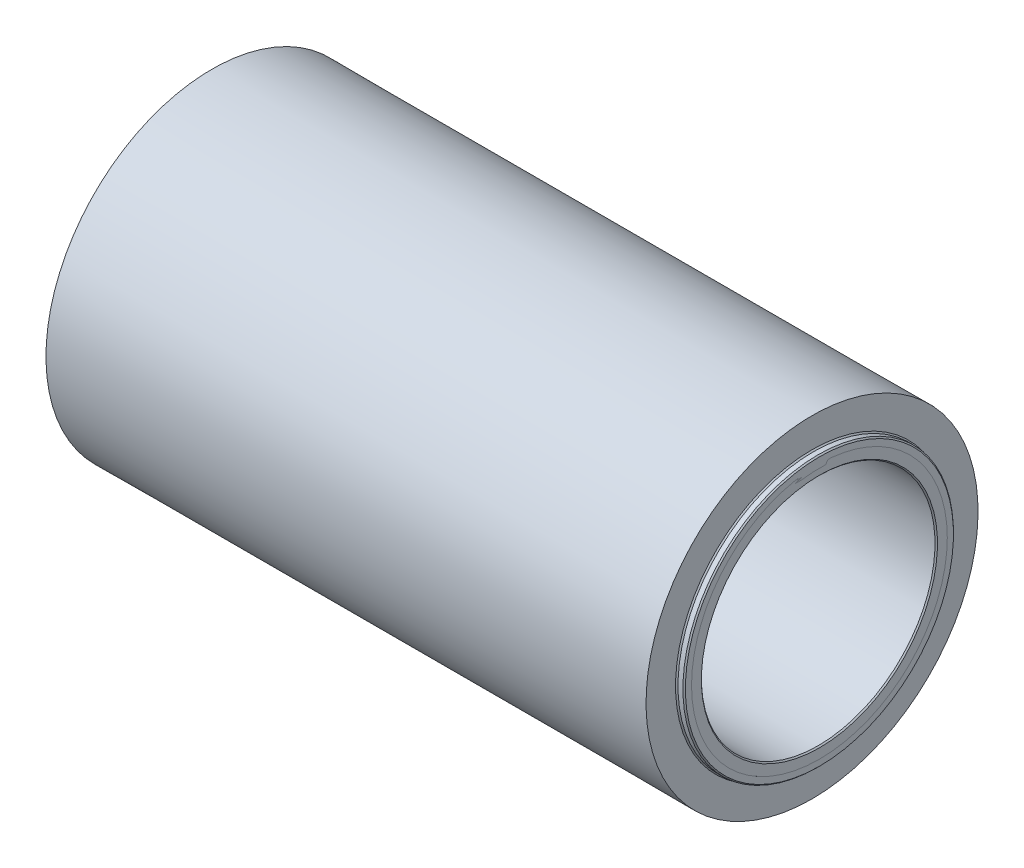
SolidWorks part; units mm, degrees
ref_plane "Front" through (0, 0, 0) normal (0, 0, 1) x (1, 0, 0)
ref_plane "Top" through (0, 0, 0) normal (0, 1, 0) x (1, 0, 0)
ref_plane "Right" through (0, 0, 0) normal (1, 0, 0) x (0, 0, -1)
sketch "Эскиз3" plane through (0, 0, 0) normal (0, 0, 1) x (1, 0, 0)
  line L0 (25.2, 10.4) -> (25.1, 10.5)
  line L1 (25.1, 10.5) -> (4.9, 10.5)
  line L2 (4.9, 10.5) -> (4.8, 10.4)
  line L3 (4.8, 10.4) -> (4.8, 10)
  line L4 (4.8, 10) -> (3.5, 10)
  line L5 (3.5, 10) -> (3.5, 10.4)
  line L6 (3.5, 10.4) -> (3.4, 10.5)
  line L7 (3.4, 10.5) -> (0.1, 10.5)
  line L8 (0.1, 10.5) -> (0, 10.4)
  line L9 (0, 10.4) -> (0, 9.5)
  line L10 (0, 9.5) -> (49.9, 9.5)
  line L11 (49.9, 9.5) -> (50, 9.6)
  line L12 (50, 9.6) -> (50, 10.4)
  line L13 (50, 10.4) -> (49.9, 10.5)
  line L14 (49.9, 10.5) -> (46.6, 10.5)
  line L15 (46.6, 10.5) -> (46.5, 10.4)
  line L16 (46.5, 10.4) -> (46.5, 10)
  line L17 (46.5, 10) -> (25.2, 10)
  line L18 (25.2, 10) -> (25.2, 10.4)
  line L19 (0, 0) -> (54.2396, 0) construction
  point P21 (54.2396, 0)
revolve "Повернуть2" add sketch "Эскиз3" angle 360 about L19
sketch "Эскиз7" plane through (0, 0, 0) normal (0, 0, 1) x (1, 0, 0)
  line L3 (0, 10.1) -> (0, 10.9)
  line L15 (50.7608, 0) -> (0, 0.0005) construction
  line L16 (50, 10.9) -> (50, 10.1)
  line L17 (49.9, 11) -> (50, 10.9)
  line L18 (49.5, 11) -> (49.9, 11)
  line L19 (49.4, 11.1) -> (49.5, 11)
  line L20 (49.4, 13.5) -> (49.4, 11.1)
  line L21 (0.6, 13.5) -> (49.4, 13.5)
  line L22 (0.6, 11.1) -> (0.6, 13.5)
  line L23 (0.5, 11) -> (0.6, 11.1)
  line L24 (0.1, 11) -> (0.5, 11)
  line L25 (0, 10.9) -> (0.1, 11)
  line L26 (0.1, 10) -> (0, 10.1)
  line L27 (49.9, 10) -> (0.1, 10)
  line L28 (50, 10.1) -> (49.9, 10)
  point P0 (50.7608, 0)
  point P6 (29.9, 10)
revolve "Повернуть3" add sketch "Эскиз7" angle 360 about L15
